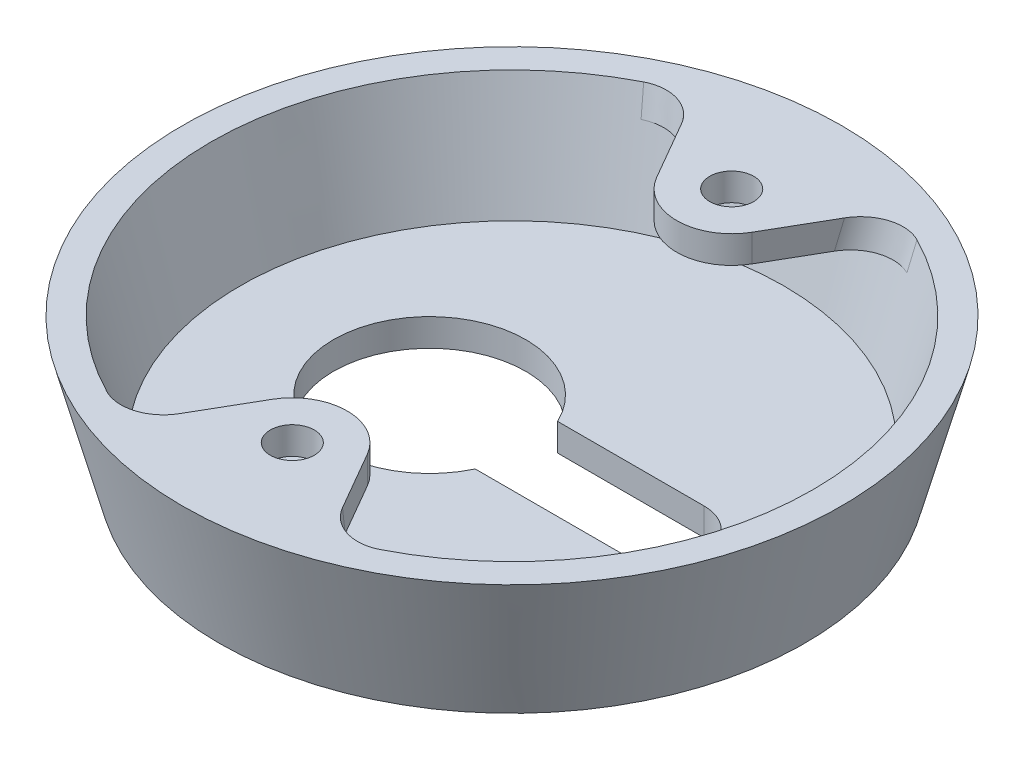
SolidWorks part; units mm, degrees
ref_plane "前视基准面" through (0, 0, 0) normal (0, 0, 1) x (1, 0, 0)
ref_plane "上视基准面" through (0, 0, 0) normal (0, 1, 0) x (1, 0, 0)
ref_plane "右视基准面" through (0, 0, 0) normal (1, 0, 0) x (0, 0, -1)
other "Configuration Table"
sketch "草图1" plane through (0, 0, 0) normal (0, 0, 1) x (1, 0, 0)
  line L0 (0, 25.1675) -> (0, -21.948) construction
  line L1 (0, 0) -> (21.3205, 0)
  line L2 (21.3205, 0) -> (24, 10)
  line L3 (24, 10) -> (21.9294, 10)
  line L4 (21.9294, 10) -> (19.7859, 2)
  line L5 (19.7859, 2) -> (0, 2)
  line L6 (0, 0) -> (0, 2)
  dimension "D1" = 2
  dimension "D2" = 2
  dimension "D3" = 10
  dimension "D4" = 75
  dimension "D5" = 48
revolve "旋转1" add sketch "草图1" angle 360 about L0
sketch "草图2" plane through (0, 2, 0) normal (0, 1, 0) x (1, 0, 0)
  line L0 (-32.2917, 0) -> (36.7934, 0) construction
  line L1 (11, 3) -> (0.3246, 3)
  line L2 (11, -3) -> (0.3246, -3)
  arc A0 (0.3246, 3) -> (0.3246, -3) centre (-6, 0) ccw
  arc A1 (11, 3) -> (11, -3) centre (11, 0) cw
  dimension "D3" = 14
  dimension "D1" = 6
  dimension "D2" = 6
  dimension "D4" = 17
extrude "切除-拉伸1" cut sketch "草图2" against normal up to next
sketch "草图3" plane through (0, 10, 0) normal (0, 1, 0) x (1, 0, 0)
  line L0 (0, 35.8137) -> (0, -43.0303) construction
  line L1 (-3.4641, 14) -> (-7.3167, 20.6729)
  line L2 (3.4641, 14) -> (7.3167, 20.6729)
  line L3 (-31.9761, 0) -> (27.8251, 0) construction
  line L4 (3.4641, -14) -> (7.3167, -20.6729)
  line L5 (-3.4641, -14) -> (-7.3167, -20.6729)
  circle A0 centre (0, 0) radius 21.9294 construction
  arc A1 (7.3167, 20.6729) -> (-7.3167, 20.6729) centre (0, 0) ccw
  arc A2 (-3.4641, 14) -> (3.4641, 14) centre (0, 16) ccw
  arc A3 (-3.4641, -14) -> (3.4641, -14) centre (0, -16) cw
  arc A4 (7.3167, -20.6729) -> (-7.3167, -20.6729) centre (0, 0) cw
  circle A5 centre (0, 16) radius 1.6
  circle A6 centre (0, -16) radius 1.6
  point P11 (0, 8)
  point P18 (0, -8)
  dimension "D2" = 4
  dimension "D3" = 3.2
  dimension "D1" = 60
  dimension "D4" = 32
extrude "凸台-拉伸1" add sketch "草图3" against normal blind 2
fillet "圆角1" radius 3 4 edges
